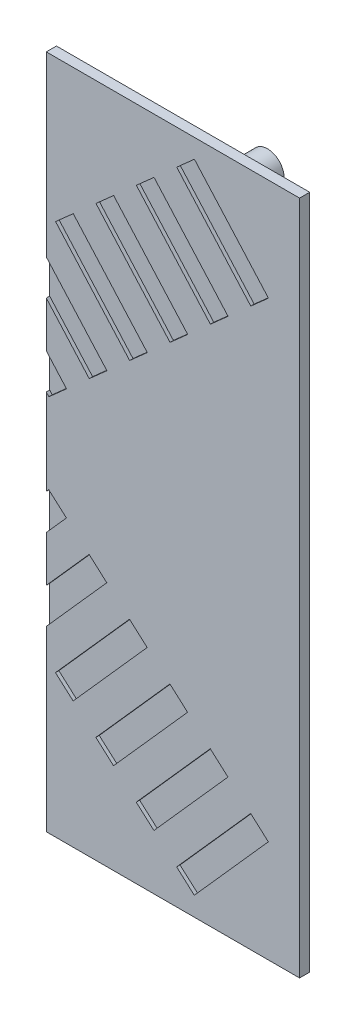
SolidWorks part; units mm, degrees
ref_plane "Front Plane" through (0, 0, 0) normal (0, 0, 1) x (1, 0, 0)
ref_plane "Top Plane" through (0, 0, 0) normal (0, 1, 0) x (1, 0, 0)
ref_plane "Right Plane" through (0, 0, 0) normal (1, 0, 0) x (0, 0, -1)
sketch "Sketch1" plane through (0, 0, 0) normal (0, 0, 1) x (1, 0, 0)
  line L1 (0, 0) -> (225, 0)
  line L2 (0, 0) -> (0, 200)
  line L3 (0, 200) -> (225, 200)
  line L4 (225, 0) -> (225, 200)
  dimension "D1" = 225
  dimension "D2" = 200
extrude "Boss-Extrude1" add sketch "Sketch1" along normal blind 3
sketch "Sketch2" plane through (0, 0, 3) normal (0, 0, 1) x (1, 0, 0)
  line L0 (0, 200) -> (225, 0) construction
  line L1 (225, 200) -> (0, 0) construction
  line L2 (21.1766, 159.1001) -> (43.1006, 183.7646)
  line L3 (9.218, 169.7299) -> (31.1421, 194.3944)
  line L4 (9.218, 169.7299) -> (14.4499, 165.0794)
  line L5 (14.4499, 165.0794) -> (36.3739, 189.7439)
  line L6 (31.1421, 194.3944) -> (36.3739, 189.7439)
  line L7 (21.1766, 159.1001) -> (26.4085, 154.4496)
  line L8 (26.4085, 154.4496) -> (48.3325, 179.1141)
  line L9 (43.1006, 183.7646) -> (48.3325, 179.1141)
  line L10 (33.1351, 148.4703) -> (55.0592, 173.1348)
  line L11 (33.1351, 148.4703) -> (38.367, 143.8197)
  line L12 (38.367, 143.8197) -> (60.291, 168.4842)
  line L13 (55.0592, 173.1348) -> (60.291, 168.4842)
  line L14 (45.0937, 137.8405) -> (67.0177, 162.505)
  line L15 (45.0937, 137.8405) -> (50.3256, 133.1899)
  line L16 (50.3256, 133.1899) -> (72.2496, 157.8544)
  line L17 (67.0177, 162.505) -> (72.2496, 157.8544)
  line L18 (57.0522, 127.2106) -> (78.9763, 151.8751)
  line L19 (57.0522, 127.2106) -> (62.2841, 122.5601)
  line L20 (62.2841, 122.5601) -> (84.2081, 147.2246)
  line L21 (78.9763, 151.8751) -> (84.2081, 147.2246)
  line L22 (69.0108, 116.5808) -> (90.9348, 141.2453)
  line L23 (69.0108, 116.5808) -> (74.2427, 111.9303)
  line L24 (74.2427, 111.9303) -> (96.1667, 136.5948)
  line L25 (90.9348, 141.2453) -> (96.1667, 136.5948)
  line L26 (80.9693, 105.951) -> (102.8933, 130.6155)
  line L27 (80.9693, 105.951) -> (86.2012, 101.3004)
  line L28 (86.2012, 101.3004) -> (108.1252, 125.965)
  line L29 (102.8933, 130.6155) -> (108.1252, 125.965)
  line L38 (116.845, 74.0615) -> (138.769, 98.726)
  line L39 (116.845, 74.0615) -> (122.0769, 69.411)
  line L40 (122.0769, 69.411) -> (144.0009, 94.0755)
  line L41 (138.769, 98.726) -> (144.0009, 94.0755)
  line L42 (128.8035, 63.4317) -> (150.7275, 88.0962)
  line L43 (128.8035, 63.4317) -> (134.0354, 58.7812)
  line L44 (134.0354, 58.7812) -> (155.9594, 83.4457)
  line L45 (150.7275, 88.0962) -> (155.9594, 83.4457)
  line L46 (140.7621, 52.8019) -> (162.6861, 77.4664)
  line L47 (140.7621, 52.8019) -> (145.994, 48.1513)
  line L48 (145.994, 48.1513) -> (167.918, 72.8158)
  line L49 (162.6861, 77.4664) -> (167.918, 72.8158)
  line L50 (152.7206, 42.1721) -> (174.6446, 66.8366)
  line L51 (152.7206, 42.1721) -> (157.9525, 37.5215)
  line L52 (157.9525, 37.5215) -> (179.8765, 62.186)
  line L53 (174.6446, 66.8366) -> (179.8765, 62.186)
  line L54 (164.6792, 31.5422) -> (186.6032, 56.2068)
  line L55 (164.6792, 31.5422) -> (169.9111, 26.8917)
  line L56 (169.9111, 26.8917) -> (191.8351, 51.5562)
  line L57 (186.6032, 56.2068) -> (191.8351, 51.5562)
  line L58 (176.6377, 20.9124) -> (198.5617, 45.5769)
  line L59 (176.6377, 20.9124) -> (181.8696, 16.2619)
  line L60 (181.8696, 16.2619) -> (203.7936, 40.9264)
  line L61 (198.5617, 45.5769) -> (203.7936, 40.9264)
  line L62 (188.5963, 10.2826) -> (210.5203, 34.9471)
  line L63 (188.5963, 10.2826) -> (193.8281, 5.6321)
  line L64 (193.8281, 5.6321) -> (215.7522, 30.2966)
  line L65 (210.5203, 34.9471) -> (215.7522, 30.2966)
  line L66 (198.5915, 154.4496) -> (176.6675, 179.1141)
  line L67 (210.5501, 165.0794) -> (188.6261, 189.7439)
  line L68 (210.5501, 165.0794) -> (215.782, 169.7299)
  line L69 (215.782, 169.7299) -> (193.8579, 194.3944)
  line L70 (188.6261, 189.7439) -> (193.8579, 194.3944)
  line L71 (198.5915, 154.4496) -> (203.8234, 159.1001)
  line L72 (203.8234, 159.1001) -> (181.8994, 183.7646)
  line L73 (176.6675, 179.1141) -> (181.8994, 183.7646)
  line L74 (186.633, 143.8197) -> (164.709, 168.4842)
  line L75 (186.633, 143.8197) -> (191.8649, 148.4703)
  line L76 (191.8649, 148.4703) -> (169.9408, 173.1348)
  line L77 (164.709, 168.4842) -> (169.9408, 173.1348)
  line L78 (174.6744, 133.1899) -> (152.7504, 157.8544)
  line L79 (174.6744, 133.1899) -> (179.9063, 137.8405)
  line L80 (179.9063, 137.8405) -> (157.9823, 162.505)
  line L81 (152.7504, 157.8544) -> (157.9823, 162.505)
  line L82 (162.7159, 122.5601) -> (140.7919, 147.2246)
  line L83 (162.7159, 122.5601) -> (167.9478, 127.2106)
  line L84 (167.9478, 127.2106) -> (146.0237, 151.8751)
  line L85 (140.7919, 147.2246) -> (146.0237, 151.8751)
  line L86 (150.7573, 111.9303) -> (128.8333, 136.5948)
  line L87 (150.7573, 111.9303) -> (155.9892, 116.5808)
  line L88 (155.9892, 116.5808) -> (134.0652, 141.2453)
  line L89 (128.8333, 136.5948) -> (134.0652, 141.2453)
  line L90 (138.7988, 101.3004) -> (116.8748, 125.965)
  line L91 (138.7988, 101.3004) -> (144.0307, 105.951)
  line L92 (144.0307, 105.951) -> (122.1067, 130.6155)
  line L93 (116.8748, 125.965) -> (122.1067, 130.6155)
  line L102 (102.9231, 69.411) -> (80.9991, 94.0755)
  line L103 (102.9231, 69.411) -> (108.155, 74.0615)
  line L104 (108.155, 74.0615) -> (86.231, 98.726)
  line L105 (80.9991, 94.0755) -> (86.231, 98.726)
  line L106 (90.9646, 58.7812) -> (69.0406, 83.4457)
  line L107 (90.9646, 58.7812) -> (96.1965, 63.4317)
  line L108 (96.1965, 63.4317) -> (74.2725, 88.0962)
  line L109 (69.0406, 83.4457) -> (74.2725, 88.0962)
  line L110 (79.006, 48.1513) -> (57.082, 72.8158)
  line L111 (79.006, 48.1513) -> (84.2379, 52.8019)
  line L112 (84.2379, 52.8019) -> (62.3139, 77.4664)
  line L113 (57.082, 72.8158) -> (62.3139, 77.4664)
  line L114 (67.0475, 37.5215) -> (45.1235, 62.186)
  line L115 (67.0475, 37.5215) -> (72.2794, 42.1721)
  line L116 (72.2794, 42.1721) -> (50.3554, 66.8366)
  line L117 (45.1235, 62.186) -> (50.3554, 66.8366)
  line L118 (55.0889, 26.8917) -> (33.1649, 51.5562)
  line L119 (55.0889, 26.8917) -> (60.3208, 31.5422)
  line L120 (60.3208, 31.5422) -> (38.3968, 56.2068)
  line L121 (33.1649, 51.5562) -> (38.3968, 56.2068)
  line L122 (43.1304, 16.2619) -> (21.2064, 40.9264)
  line L123 (43.1304, 16.2619) -> (48.3623, 20.9124)
  line L124 (48.3623, 20.9124) -> (26.4383, 45.5769)
  line L125 (21.2064, 40.9264) -> (26.4383, 45.5769)
  line L126 (31.1719, 5.6321) -> (9.2478, 30.2966)
  line L127 (31.1719, 5.6321) -> (36.4037, 10.2826)
  line L128 (36.4037, 10.2826) -> (14.4797, 34.9471)
  line L129 (9.2478, 30.2966) -> (14.4797, 34.9471)
  line L130 (92.9279, 95.3212) -> (114.8519, 119.9857) [skipped]
  line L131 (98.1598, 90.6706) -> (120.0838, 115.3351) [skipped]
  line L132 (114.8519, 119.9857) -> (120.0838, 115.3351) [skipped]
  line L133 (126.8402, 90.6706) -> (104.9162, 115.3351) [skipped]
  line L134 (132.0721, 95.3212) -> (110.1481, 119.9857) [skipped]
  line L135 (104.9162, 115.3351) -> (110.1481, 119.9857) [skipped]
  line L136 (104.8864, 84.6914) -> (126.8104, 109.3559) [skipped]
  line L137 (104.8864, 84.6914) -> (110.1183, 80.0408) [skipped]
  line L138 (110.1183, 80.0408) -> (132.0423, 104.7053) [skipped]
  line L139 (114.8817, 80.0408) -> (92.9577, 104.7053) [skipped]
  line L140 (114.8817, 80.0408) -> (120.1136, 84.6914) [skipped]
  line L141 (120.1136, 84.6914) -> (98.1896, 109.3559) [skipped]
  line L142 (126.8402, 90.6706) -> (132.0721, 95.3212) [skipped]
  line L143 (126.8104, 109.3559) -> (132.0423, 104.7053) [skipped]
  line L144 (92.9577, 104.7053) -> (98.1896, 109.3559) [skipped]
  line L145 (92.9279, 95.3212) -> (98.1598, 90.6706) [skipped]
  point P12 (20.1801, 182.0622)
  point P79 (199.5881, 177.4116)
  dimension "D1" = 33
  dimension "D2" = 7
  dimension "D3" = 33
  dimension "D5" = 27
  dimension "D6" = 33
  dimension "D7" = 7
  dimension "D8" = 33
  dimension "D9" = 27
  dimension "D4" = 16
  dimension "D10" = 16
extrude "Cut-Extrude1" cut sketch "Sketch2" against normal blind 1
sketch "Sketch4" plane through (0, 0, 0) normal (0, 0, -1) x (-1, 0, 0)
  line L0 (0, 200) -> (0, 0) construction
  line L1 (-212.5, 200) -> (-12.5, 200)
  line L2 (-212.5, 200) -> (-212.5, 0)
  line L3 (-212.5, 0) -> (-12.5, 0)
  line L4 (-12.5, 200) -> (-12.5, 0)
  line L5 (0, 0) -> (-225, 0) construction
  line L9 (-225, 200) -> (-150, 200)
  line L10 (-225, 200) -> (-225, 0)
  line L11 (-225, 0) -> (-150, 0)
  line L12 (-150, 200) -> (-150, 0)
  circle A0 centre (-202.5, 190) radius 4.9
  circle A1 centre (-162.5, 10) radius 4.9
  dimension "D4" = 40
  dimension "D5" = 9.8
  dimension "D6" = 10
  dimension "D7" = 10
  dimension "D8" = 10
  dimension "D9" = 12.5
  dimension "D1" = 9.8
  dimension "D2" = 12.5
  dimension "D3" = 75
extrude "Boss-Extrude2" add sketch "Sketch4" along normal blind 10 contours A0 | A1
sketch "Sketch5" plane through (0, 0, 0) normal (0, 0, -1) x (-1, 0, 0)
  line L0 (0, 0) -> (-225, 0) construction
  line L1 (0, 200) -> (-150, 200)
  line L2 (0, 200) -> (0, 0)
  line L3 (0, 0) -> (-150, 0)
  line L4 (-150, 200) -> (-150, 0)
  dimension "D1" = 150
extrude "Cut-Extrude2" cut sketch "Sketch5" against normal blind 10
